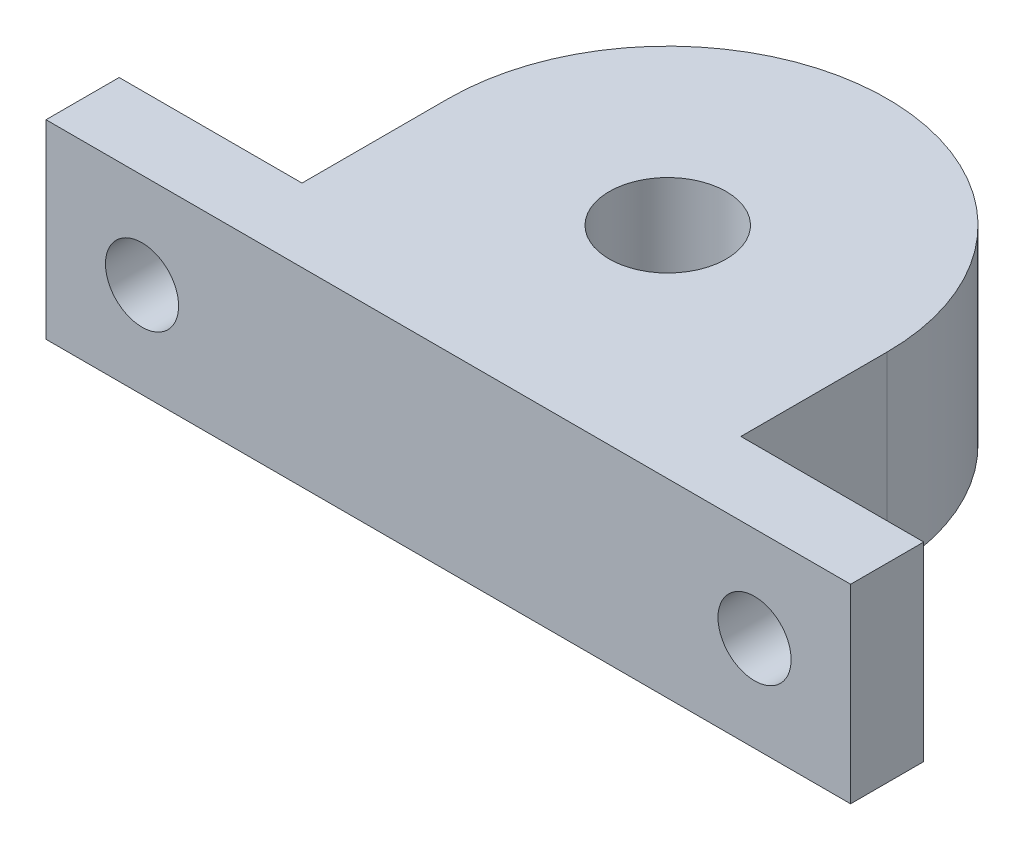
SolidWorks part; units mm, degrees
material "Gray Cast Iron"
ref_plane "Front Plane" through (0, 0, 0) normal (0, 0, 1) x (1, 0, 0)
ref_plane "Top Plane" through (0, 0, 0) normal (0, 1, 0) x (1, 0, 0)
ref_plane "Right Plane" through (0, 0, 0) normal (1, 0, 0) x (0, 0, -1)
sketch "Sketch1" plane through (0, 0, 0) normal (0, 1, 0) x (1, 0, 0)
  line L0 (-15, 0) -> (-15, -10)
  line L1 (-15, -10) -> (-27.5, -10)
  line L2 (-27.5, -10) -> (-27.5, -15)
  line L3 (-27.5, -15) -> (27.5, -15)
  line L4 (27.5, -15) -> (27.5, -10)
  line L5 (27.5, -10) -> (15, -10)
  line L6 (15, -10) -> (15, 0)
  line L7 (0, 0) -> (0, -15) construction
  circle A0 centre (0, 0) radius 4
  arc A1 (15, 0) -> (-15, 0) centre (0, 0) ccw
  point P3 (15, 0)
  dimension "D1" = 8
  dimension "D2" = 15
  dimension "D3" = 5
  dimension "D4" = 55
extrude "Boss-Extrude1" add sketch "Sketch1" along normal blind 13
hole_wizard "M4 Clearance Hole1" positions "Sketch2" profile "Sketch3" hole size "M4" standard "ANSI Metric" end condition through all
sketch "Sketch2" plane through (0, 0, 10) normal (0, 0, -1) x (-1, 0, 0)
  line L1 (-27.5, 6.5) -> (27.5, 6.5) construction
  line L2 (-27.5, 13) -> (-27.5, 0) construction
  line L3 (27.5, 13) -> (27.5, 0) construction
  point P0 (-20.935, 6.5)
  point P2 (20.935, 6.5)
  point P32 (0, 6.5)
  dimension "D1" = 41.87
  dimension "D2" = 20.935
sketch "Sketch3" plane through (20.935, 6.5, 10) normal (1, 0, 0) x (0, 1, 0)
  line L0 (0, 0) -> (0, 5)
  line L1 (0, 5) -> (2.5, 5)
  line L2 (2.5, 5) -> (2.5, 0)
  line L5 (2.5, 0) -> (0, 0)
  line L11 (0, -6.35) -> (0, 107.95) construction
  dimension "Thru Hole Dia." = 5
  dimension "Thru Hole Depth" = 5
